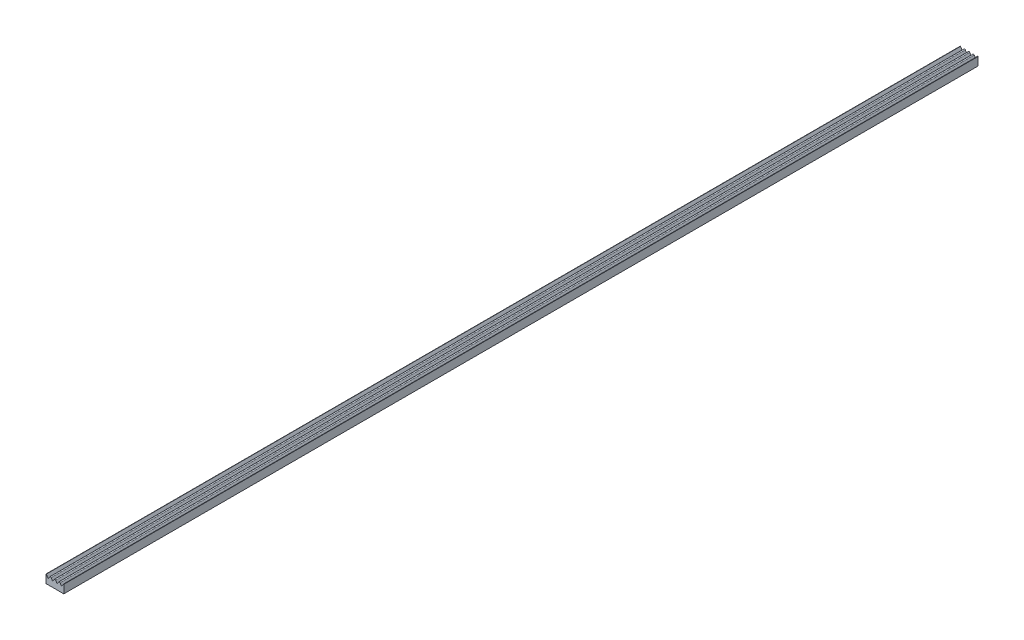
SolidWorks part; units mm, degrees
material "Polyurethane Foam Flexible"
ref_plane "Front Plane" through (0, 0, 0) normal (0, 0, 1) x (1, 0, 0)
ref_plane "Top Plane" through (0, 0, 0) normal (0, 1, 0) x (1, 0, 0)
ref_plane "Right Plane" through (0, 0, 0) normal (1, 0, 0) x (0, 0, -1)
sketch "Sketch1" plane through (0, 0, 0) normal (0, 0, 1) x (1, 0, 0)
  line L0 (-12.7, 6.35) -> (0, 6.35) construction
  line L1 (0, 0) -> (-12.7, 0)
  line L2 (0, 0) -> (0, 5.9072)
  line L3 (-6.35, 0) -> (-6.35, 6.35) construction
  line L4 (-12.7, 0) -> (-12.7, 5.9072)
  line L5 (-12.7, 3.81) -> (0, 3.81) construction
  line L6 (-7.9375, 3.81) -> (-6.8885, 5.4884)
  line L7 (-7.9375, 3.81) -> (-8.9865, 5.4884)
  line L8 (-10.0635, 5.4884) -> (-11.1125, 3.81)
  line L9 (-11.1125, 3.81) -> (-12.4653, 5.9745)
  line L10 (-4.7625, 3.81) -> (-5.8115, 5.4884)
  line L11 (-4.7625, 3.81) -> (-3.7135, 5.4884)
  line L14 (-2.6365, 5.4884) -> (-1.5875, 3.81)
  line L15 (-1.5875, 3.81) -> (-0.2347, 5.9745)
  arc A0 (-3.7135, 5.4884) -> (-2.6365, 5.4884) centre (-3.175, 5.1519) cw
  arc A1 (-6.8885, 5.4884) -> (-5.8115, 5.4884) centre (-6.35, 5.1519) cw
  arc A2 (-8.9865, 5.4884) -> (-10.0635, 5.4884) centre (-9.525, 5.1519) ccw
  arc A3 (0, 5.9072) -> (-0.2347, 5.9745) centre (-0.127, 5.9072) ccw
  arc A4 (-12.4653, 5.9745) -> (-12.7, 5.9072) centre (-12.573, 5.9072) ccw
  dimension "D7" = 0.635
  dimension "D8" = 0.127
  dimension "D1" = 6.35
  dimension "D2" = 12.7
  dimension "D3" = 1.5875
  dimension "D4" = 2.54
  dimension "D5" = 1.5875
extrude "Boss-Extrude1" add sketch "Sketch1" along normal blind 652.145
